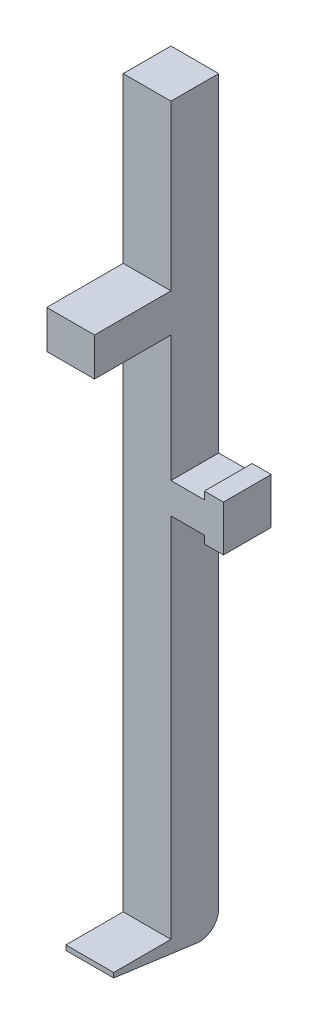
SolidWorks part; units mm, degrees
ref_plane "Front Plane" through (0, 0, 0) normal (0, 0, 1) x (1, 0, 0)
ref_plane "Top Plane" through (0, 0, 0) normal (0, 1, 0) x (1, 0, 0)
ref_plane "Right Plane" through (0, 0, 0) normal (1, 0, 0) x (0, 0, -1)
sketch "Sketch2" plane through (0, 0, 0) normal (0, 1, 0) x (1, 0, 0)
  line L1 (-1.25, -1.25) -> (1.25, -1.25)
  line L2 (-1.25, -1.25) -> (-1.25, 1.25)
  line L3 (-1.25, 1.25) -> (1.25, 1.25)
  line L4 (1.25, -1.25) -> (1.25, 1.25)
  line L5 (-1.25, -1.25) -> (1.25, 1.25) construction
  line L6 (-1.25, 1.25) -> (1.25, -1.25) construction
  point P0 (0, 0)
  dimension "D1" = 2.5
  dimension "D2" = 2.5
extrude "Boss-Extrude1" add sketch "Sketch2" along normal blind 39
sketch "Sketch3" plane through (0, 0, 1.25) normal (0, 0, 1) x (1, 0, 0)
  line L0 (1.25, 39) -> (1.25, 0) construction
  line L1 (-1.25, 0) -> (1.25, 0)
  line L2 (-1.25, 0) -> (-1.25, 1)
  line L3 (-1.25, 1) -> (1.25, 1)
  line L4 (1.25, 0) -> (1.25, 1)
  dimension "D1" = 1
extrude "Boss-Extrude2" add sketch "Sketch3" along normal blind 3 contours L3 L4 L1 L2
sketch "Sketch4" plane through (1.25, 0, 0) normal (1, 0, 0) x (0, 0, -1)
  line L0 (-4.25, 0) -> (-4.25, 0.75)
  line L1 (-4.25, 0) -> (-4.25, 1) construction
  line L2 (-4.25, 0.75) -> (1.25, 0)
  line L3 (1.25, 0) -> (-4.25, 0)
  dimension "D1" = 0.75
extrude "Cut-Extrude1" cut sketch "Sketch4" against normal up to vertex (2.5 mm away)
fillet "Fillet1" radius 1 1 edges at (0, 0, -1.25)
sketch "Sketch6" plane through (0, 0, 1.25) normal (0, 0, 1) x (1, 0, 0)
  line L1 (1.25, 39) -> (1.25, 1) construction
  line L2 (1.25, 20.2) -> (1.25, 21.8)
  line L3 (1.25, 21.8) -> (3, 21.8)
  line L4 (3, 21.8) -> (3, 22.2)
  line L5 (3, 22.2) -> (4, 22.2)
  line L6 (4, 22.2) -> (4, 19.8)
  line L8 (3, 19.8) -> (4, 19.8)
  line L9 (3, 20.2) -> (3, 19.8)
  line L10 (1.25, 20.2) -> (3, 20.2)
  point P0 (1.25, 21)
  dimension "D1" = 20
  dimension "D2" = 1.75
  dimension "D3" = 1
extrude "Boss-Extrude3" add sketch "Sketch6" against normal up to vertex (2.5 mm away) contours L3 L4 L5 L6 L8 L9 L10 L2
sketch "Sketch8" plane through (0, 0, 1.25) normal (0, 0, 1) x (1, 0, 0)
  line L0 (1.25, 39) -> (1.25, 21.8) construction
  line L1 (1.25, 30.4) -> (-1.25, 30.4)
  line L2 (1.25, 30.4) -> (1.25, 28.4)
  line L3 (1.25, 28.4) -> (-1.25, 28.4)
  line L4 (-1.25, 30.4) -> (-1.25, 28.4)
  line L5 (-1.25, 39) -> (-1.25, 1) construction
  dimension "D1" = 2
extrude "Boss-Extrude4" add sketch "Sketch8" along normal blind 4
